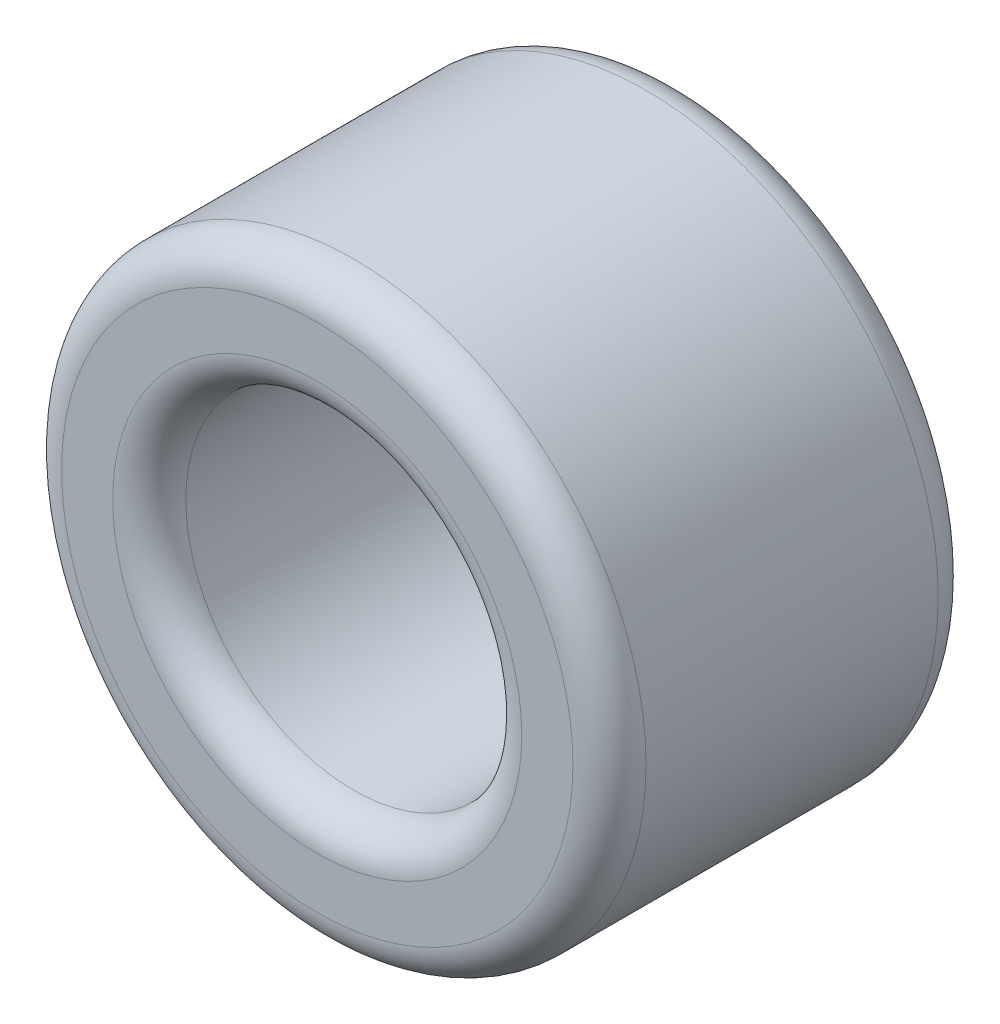
SolidWorks part; units mm, degrees
ref_plane "前视基准面" through (0, 0, 0) normal (0, 0, 1) x (1, 0, 0)
ref_plane "上视基准面" through (0, 0, 0) normal (0, 1, 0) x (1, 0, 0)
ref_plane "右视基准面" through (0, 0, 0) normal (1, 0, 0) x (0, 0, -1)
other "Configuration Table"
sketch "草图1" plane through (0, 0, 0) normal (0, 0, 1) x (1, 0, 0)
  circle A0 centre (0, 0) radius 2.3
  circle A1 centre (0, 0) radius 4
  dimension "D1" = 4.6
extrude "凸台-拉伸1" add sketch "草图1" along normal blind 5
fillet "圆角1" radius 0.5 4 edges at (2.3, 0, 0) (4, 0, 0) (2.3, 0, 5) (4, 0, 5)
